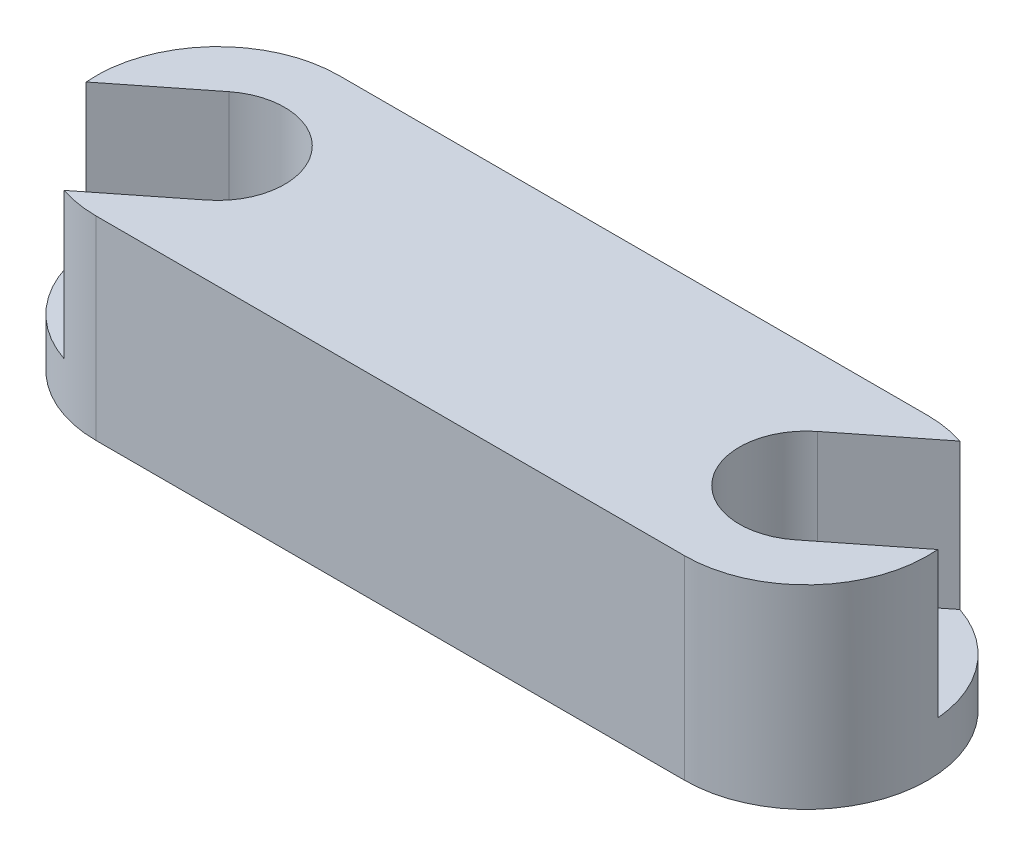
SolidWorks part; units mm, degrees
ref_plane "Front Plane" through (0, 0, 0) normal (0, 0, 1) x (1, 0, 0)
ref_plane "Top Plane" through (0, 0, 0) normal (0, 1, 0) x (1, 0, 0)
ref_plane "Right Plane" through (0, 0, 0) normal (1, 0, 0) x (0, 0, -1)
sketch "Sketch1" plane through (0, 0, 0) normal (0, 1, 0) x (1, 0, 0)
  line L0 (-7.7125, 6.5) -> (16.4949, 6.5)
  line L1 (-7.7125, -3.5) -> (16.4949, -3.5)
  arc A0 (-7.7125, 6.5) -> (-7.7125, -3.5) centre (-7.7125, 1.5) ccw
  arc A1 (16.4949, -3.5) -> (16.4949, 6.5) centre (16.4949, 1.5) ccw
  circle A2 centre (-7.7125, 1.5) radius 2.75
  circle A3 centre (16.4949, 1.5) radius 2.75
  dimension "D3" = 5.5
  dimension "D4" = 5.5
  dimension "D5" = 5
  dimension "D2" = 24.2074
extrude "Boss-Extrude1" add sketch "Sketch1" along normal blind 8
sketch "Sketch2" plane through (0, 8, 0) normal (0, 1, 0) x (1, 0, 0)
  line L0 (4.3912, 6.5) -> (4.3912, -6.8516) construction
  line L5 (16.4949, 6.5) -> (-7.7125, 6.5) construction
  line L10 (16.4949, 1.5) -> (-7.7125, 1.5) construction
  line L11 (14.7909, 3.6584) -> (18.1989, -0.6584)
  line L12 (14.7909, 3.6584) -> (24.7217, 11.4986)
  line L13 (18.1989, -0.6584) -> (28.1298, 7.1817)
  line L14 (24.7217, 11.4986) -> (28.1298, 7.1817)
  line L15 (21.4949, 1.5) -> (27.9244, 1.5) construction
  line L18 (-9.4165, -0.6584) -> (-19.3474, 7.1817) construction
  line L19 (-15.9394, 11.4986) -> (-19.3474, 7.1817) construction
  line L20 (-6.0085, 3.6584) -> (-15.9394, 11.4986) construction
  line L21 (-6.0085, 3.6584) -> (-9.4165, -0.6584) construction
  line L22 (-6.0085, -0.6584) -> (-9.4165, 3.6584)
  line L23 (-6.0085, -0.6584) -> (-15.9394, -8.4986)
  line L24 (-15.9394, -8.4986) -> (-19.3474, -4.1817)
  line L25 (-9.4165, 3.6584) -> (-19.3474, -4.1817)
  circle A1 centre (16.4949, 1.5) radius 2.75 construction
  arc A2 (16.4949, -3.5) -> (16.4949, 6.5) centre (16.4949, 1.5) ccw construction
  dimension "D2" = 12.6527
  dimension "D3" = 38.29
extrude "Cut-Extrude1" cut sketch "Sketch2" against normal blind 6
